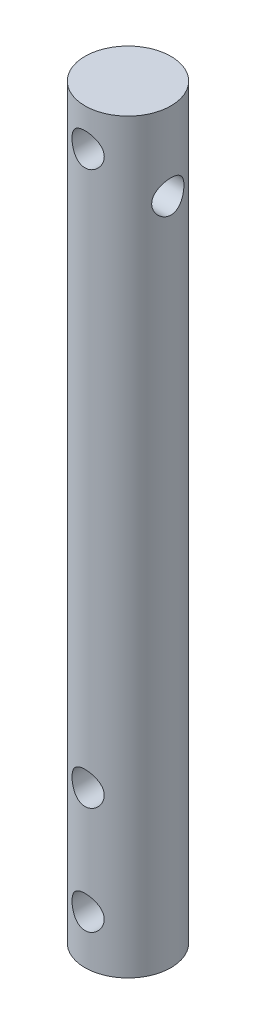
SolidWorks part; units mm, degrees
ref_plane "Front Plane" through (0, 0, 0) normal (0, 0, 1) x (1, 0, 0)
ref_plane "Top Plane" through (0, 0, 0) normal (0, 1, 0) x (1, 0, 0)
ref_plane "Right Plane" through (0, 0, 0) normal (1, 0, 0) x (0, 0, -1)
sketch "Sketch1" plane through (0, 0, 0) normal (0, 1, 0) x (1, 0, 0)
  circle A0 centre (0, 0) radius 4
  dimension "D1" = 8
extrude "Boss-Extrude1" add sketch "Sketch1" along normal blind 69.5
sketch "Sketch2" plane through (-34.8009, 1.7015, 0) normal (0, 0, 1) x (1, 0, 0)
  circle A1 centre (34.8009, 2.7985) radius 1.5
  circle A2 centre (34.8009, 12.7985) radius 1.5
  dimension "D1" = 4.5
  dimension "D4" = 2
extrude "Cut-Extrude1" cut sketch "Sketch2" against normal through all both and the other way through all
sketch "Sketch3" plane through (0, 0, 0) normal (0, 0, 1) x (1, 0, 0)
  line L4 (4, 69.5) -> (-4, 69.5) construction
  circle A0 centre (0, 66) radius 1.5
  point P2 (-0.1477, 69.4406)
  point P5 (0, 0)
  dimension "D1" = 3.5
  dimension "D2" = 3
extrude "Cut-Extrude2" cut sketch "Sketch3" against normal through all both and the other way through all
sketch "Sketch4" plane through (0, 0, 0) normal (1, 0, 0) x (0, 0, -1)
  line L1 (4, 69.5) -> (-4, 69.5) construction
  circle A0 centre (0, 62.2) radius 1.5
  dimension "D2" = 3
  dimension "D1" = 7.3
extrude "Cut-Extrude3" cut sketch "Sketch4" against normal through all both and the other way through all
